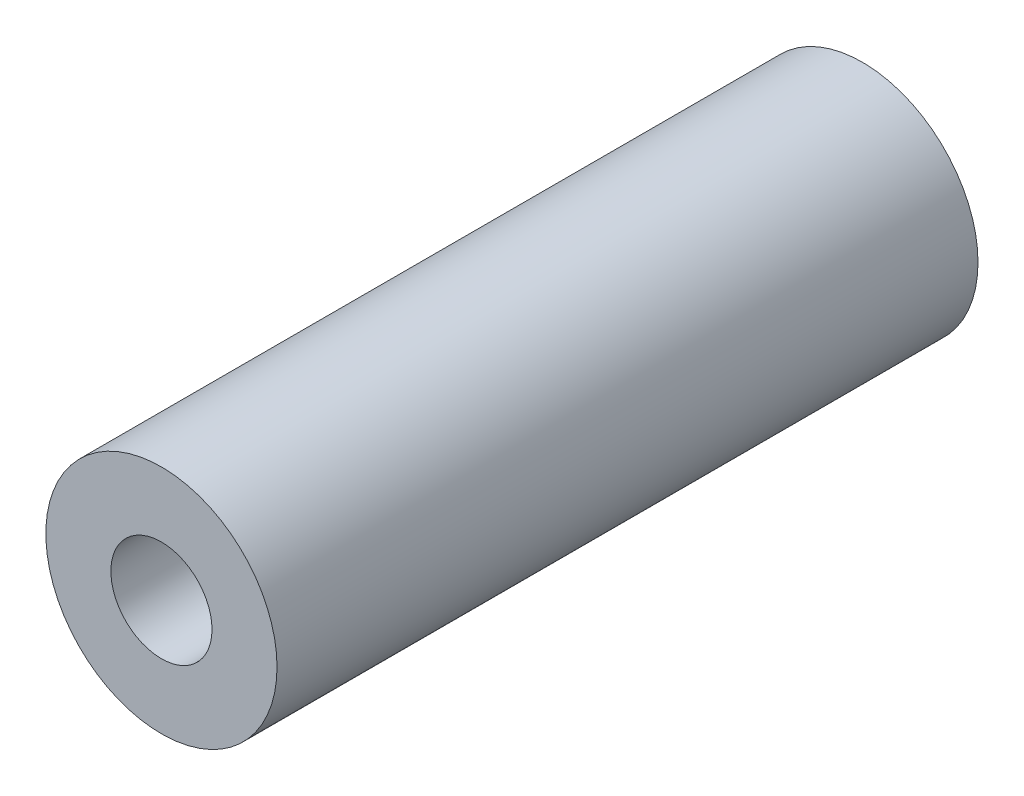
SolidWorks part; units mm, degrees
ref_plane "Plan de face" through (0, 0, 0) normal (0, 0, 1) x (1, 0, 0)
ref_plane "Plan de dessus" through (0, 0, 0) normal (0, 1, 0) x (1, 0, 0)
ref_plane "Plan de droite" through (0, 0, 0) normal (1, 0, 0) x (0, 0, -1)
sketch "Esquisse1" plane through (0, 0, 0) normal (0, 0, 1) x (1, 0, 0)
  circle A0 centre (0, 0) radius 3.5
  circle A1 centre (0, 0) radius 8
  dimension "D1" = 7
  dimension "D2" = 16
extrude "Boss.-Extru.1" add sketch "Esquisse1" along normal blind 48.514
